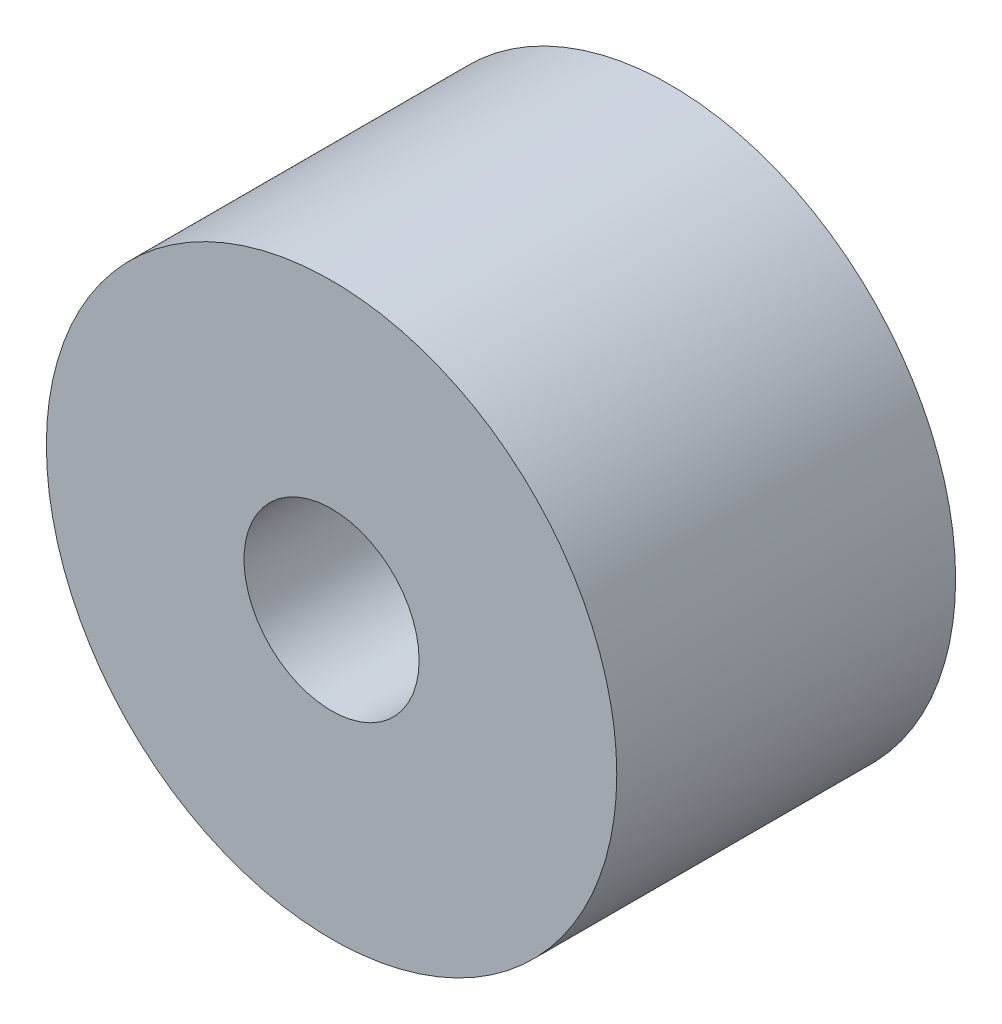
SolidWorks part; units mm, degrees
ref_plane "Płaszczyzna przednia" through (0, 0, 0) normal (0, 0, 1) x (1, 0, 0)
ref_plane "Płaszczyzna górna" through (0, 0, 0) normal (0, 1, 0) x (1, 0, 0)
ref_plane "Płaszczyzna prawa" through (0, 0, 0) normal (1, 0, 0) x (0, 0, -1)
sketch "Szkic1" plane through (0, 0, 0) normal (0, 0, 1) x (1, 0, 0)
  circle A0 centre (200.5272, 1578.6766) radius 5.05
  circle A1 centre (200.5272, 1578.6766) radius 1.55
  dimension "D1" = 10.1
  dimension "D2" = 3.1
extrude "Dodanie-wyciągnięcie1" add sketch "Szkic1" along normal blind 6
